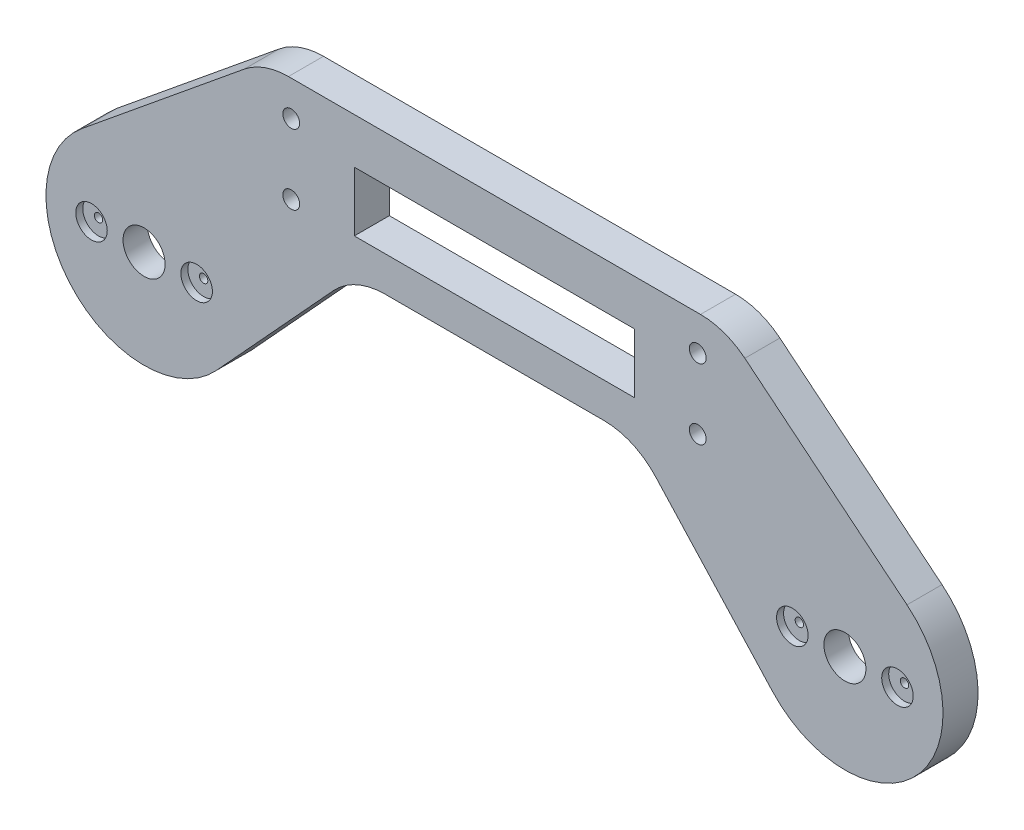
SolidWorks part; units mm, degrees
ref_plane "前视基准面" through (0, 0, 0) normal (0, 0, 1) x (1, 0, 0)
ref_plane "上视基准面" through (0, 0, 0) normal (0, 1, 0) x (1, 0, 0)
ref_plane "右视基准面" through (0, 0, 0) normal (1, 0, 0) x (0, 0, -1)
sketch "草图3" plane through (0, 0, 0) normal (0, 0, 1) x (1, 0, 0)
  line L0 (-35.7232, 7.7438) -> (-58.858, -11.1586)
  line L1 (-15.6022, -10) -> (15.6022, -10)
  line L3 (-29.3961, 10) -> (29.3961, 10)
  line L5 (-32.9619, -10) -> (32.9619, 10) construction
  line L6 (-32.9619, 10) -> (27.0109, -8.1946) construction
  line L7 (35.7232, 7.7438) -> (58.858, -11.1586)
  line L8 (-22.9724, -13.2413) -> (-39.6818, -31.4622)
  line L9 (22.9724, -13.2413) -> (39.6818, -31.4622)
  arc A0 (39.6818, -31.4622) -> (58.858, -11.1586) centre (50, -22) ccw
  arc A1 (-58.858, -11.1586) -> (-39.6818, -31.4622) centre (-50, -22) ccw
  arc A2 (15.6022, -10) -> (22.9724, -13.2413) centre (15.6022, -20) cw
  arc A3 (-15.6022, -10) -> (-22.9724, -13.2413) centre (-15.6022, -20) ccw
  arc A4 (35.7232, 7.7438) -> (29.3961, 10) centre (29.3961, 0) ccw
  arc A5 (-29.3961, 10) -> (-35.7232, 7.7438) centre (-29.3961, 0) ccw
  point P0 (0, 0)
  point P8 (0, 10)
  dimension "D1" = 100
  dimension "D8" = 28
  dimension "D9" = 28
  dimension "D3" = 10
  dimension "D2" = 50
  dimension "D4" = 0
  dimension "D5" = 60
  dimension "D6" = 20
extrude "凸台-拉伸1" add sketch "草图3" along normal blind 5
sketch "草图4" plane through (0, 0, 5) normal (0, 0, 1) x (1, 0, 0)
  line L0 (-15.6022, -10) -> (15.6022, -10) construction
  line L1 (-20, -5) -> (20, -5)
  line L2 (-20, -5) -> (-20, 3.5)
  line L3 (-20, 3.5) -> (20, 3.5)
  line L4 (20, -5) -> (20, 3.5)
  point P7 (0, -5)
  dimension "D1" = 40
  dimension "D2" = 8.5
  dimension "D3" = 5
  dimension "D4" = 0
extrude "切除-拉伸1" cut sketch "草图4" against normal blind 5
sketch "草图5" plane through (0, 0, 5) normal (0, 0, 1) x (1, 0, 0)
  line L0 (-20, -5) -> (20, -5) construction
  line L1 (-15.6022, -10) -> (15.6022, -10) construction
  circle A0 centre (-29, -5) radius 1.2
  circle A1 centre (-29, 5) radius 1.2
  point P6 (0, -5)
  dimension "D1" = 2.4
  dimension "D2" = 2.4
  dimension "D3" = 29
  dimension "D4" = 29
  dimension "D5" = 5
  dimension "D6" = 10
extrude "切除-拉伸2" cut sketch "草图5" against normal blind 7
sketch "草图9" plane through (0, 0, 0) normal (0, 0, -1) x (-1, 0, 0)
  circle A0 centre (-50, -22) radius 9
  dimension "D1" = 18
ref_plane "基准面3" through (0, 0, 0) normal (-1, 0, 0) x (0, 0, 1)
mirror "镜向1" about plane through (0, 0, 0) normal (-1, 0, 0) of "切除-拉伸2"
extrude "切除-拉伸3" cut sketch "草图9" against normal blind 1.5
sketch "草图10" plane through (0, 0, 1.5) normal (0, 0, -1) x (-1, 0, 0)
  circle A0 centre (-50, -22) radius 3
  circle A2 centre (-57.5, -22) radius 0.6
  circle A3 centre (-42.5, -22) radius 0.6
  dimension "D1" = 7.5
  dimension "D2" = 7.5
extrude "切除-拉伸4" cut sketch "草图10" against normal blind 5
mirror "镜向3" about plane through (0, 0, 0) normal (-1, 0, 0) of "切除-拉伸3", "切除-拉伸4"
sketch "草图11" plane through (0, 0, 5) normal (0, 0, 1) x (1, 0, 0)
  circle A0 centre (-57.5, -22) radius 2.25
  circle A1 centre (-42.5, -22) radius 2.25
extrude "切除-拉伸5" cut sketch "草图11" against normal blind 1
mirror "镜向4" about plane through (0, 0, 0) normal (-1, 0, 0) of "切除-拉伸5"
